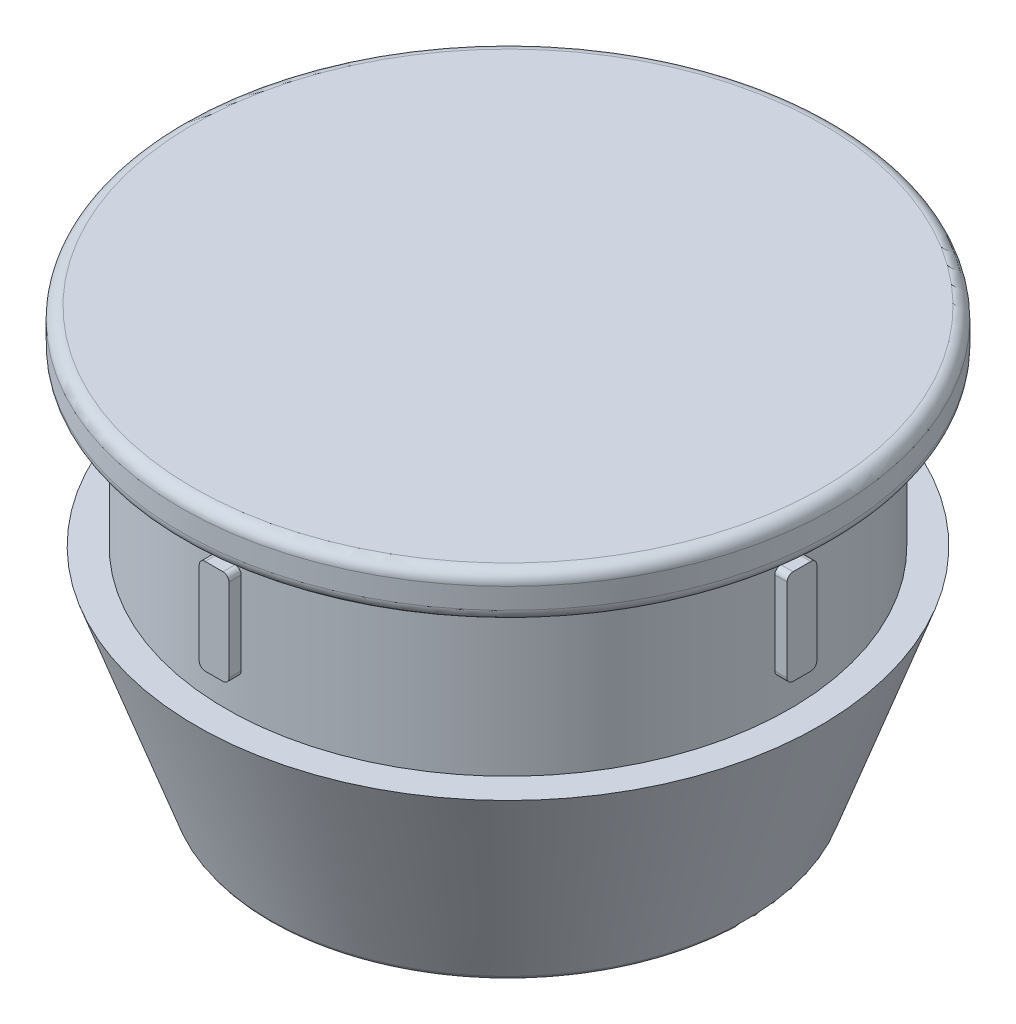
SolidWorks part; units mm, degrees
ref_plane "Front Plane" through (0, 0, 0) normal (0, 0, 1) x (1, 0, 0)
ref_plane "Top Plane" through (0, 0, 0) normal (0, 1, 0) x (1, 0, 0)
ref_plane "Right Plane" through (0, 0, 0) normal (1, 0, 0) x (0, 0, -1)
sketch "Sketch1" plane through (0, 0, 0) normal (0, 0, 1) x (1, 0, 0)
  line L0 (0, 0) -> (0, 129331.7353) construction
  line L1 (13.335, -6.985) -> (10.16, -15.875)
  line L2 (-12.7, -25.4) -> (12.7, -25.4) construction
  line L3 (-12.7, -25.4) -> (-12.7, 0) construction
  line L5 (12.7, -25.4) -> (12.7, 0) construction
  line L7 (10.16, -15.875) -> (9.525, -15.875)
  line L8 (9.525, -15.875) -> (9.525, 0)
  line L9 (9.525, 0) -> (0, 0)
  line L10 (0, 0) -> (0, 1.905)
  line L11 (0, 1.905) -> (13.97, 1.905)
  line L12 (12.065, 0) -> (12.065, -6.985)
  line L13 (12.065, -6.985) -> (13.335, -6.985)
  line L14 (12.065, 0) -> (13.97, 0)
  line L15 (13.97, 0) -> (13.97, 1.905)
  point P3 (0, 0)
  point P8 (0, 0)
  point P10 (0, -25.4)
  point P20 (13.587, 0)
  dimension "D1" = 25.4
  dimension "D2" = 25.4
  dimension "D3" = 26.67
  dimension "D4" = 8.89
  dimension "D5" = 1.905
  dimension "D6" = 2.54
  dimension "D7" = 20.32
  dimension "D8" = 24.13
  dimension "D9" = 17.78
  dimension "D10" = 27.94
revolve "Revolve1" add sketch "Sketch1" angle 360 about L0
ref_plane "Plane1" through (9.525, 0, 0) normal (-1, 0, 0) x (0, 0, 1)
sketch "Sketch2" plane through (9.525, 0, 0) normal (-1, 0, 0) x (0, 0, 1)
  line L0 (0, 0) -> (0, -6.985) construction
  line L1 (0.635, -1.4605) -> (-0.635, -1.4605)
  line L2 (0.635, -1.4605) -> (0.635, -5.5245)
  line L3 (0.635, -5.5245) -> (-0.635, -5.5245)
  line L4 (-0.635, -1.4605) -> (-0.635, -5.5245)
  line L5 (0.635, -1.4605) -> (-0.635, -5.5245) construction
  line L6 (0.635, -5.5245) -> (-0.635, -1.4605) construction
  line L7 (13.335, -6.985) -> (-13.335, -6.985) construction
  point P0 (0, -3.4925)
  point P8 (0, 0)
  point P9 (0, -3.4925)
  point P10 (0, 0)
  point P11 (0, 0)
  point P14 (0, 0)
  dimension "D1" = 4.064
  dimension "D2" = 1.27
extrude "Boss-Extrude1" add sketch "Sketch2" against normal blind 3.048
fillet "Fillet1" radius 0.508 4 edges at (0, 1.905, -13.97) (0, 0, -13.97) (0, 0, -9.525) (0, 0, -12.065)
fillet "Fillet2" radius 0.254 6 edges at (0, -15.875, -9.525) (0, -15.875, -10.16) (12.3106, -5.5245, 0.635) (12.3106, -1.4605, 0.635) (12.3106, -1.4605, -0.635) (12.3106, -5.5245, -0.635)
pattern_circular "CirPattern1" count 4 every 90 about axis through (0, 0, 0) along (0, 1, 0) of "Boss-Extrude1", "Fillet2"
